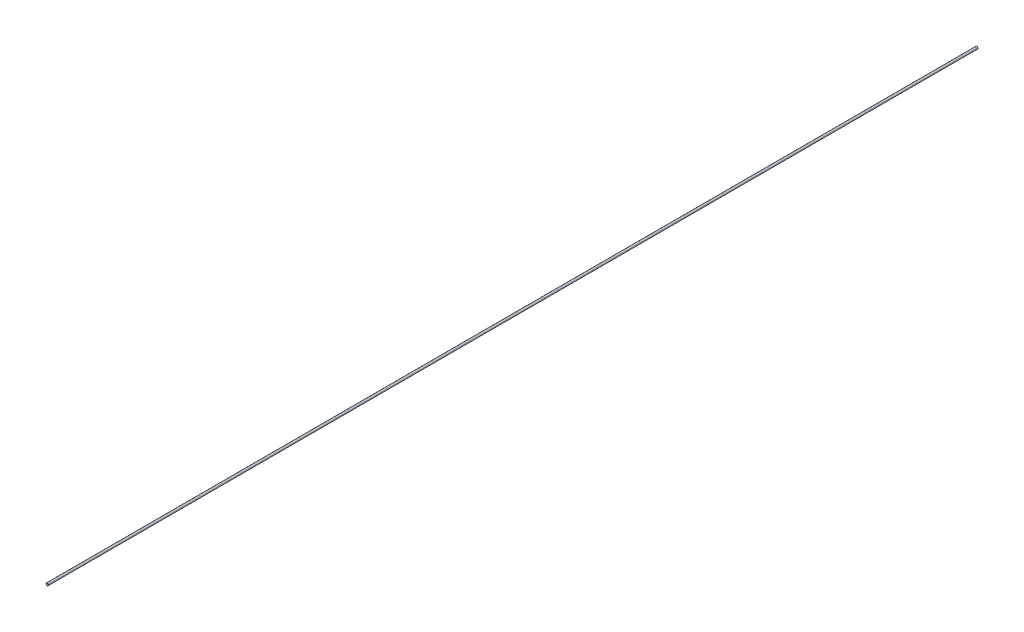
SolidWorks part; units mm, degrees
material "6061-T6 (SS)"
ref_plane "Front Plane" through (0, 0, 0) normal (0, 0, 1) x (1, 0, 0)
ref_plane "Top Plane" through (0, 0, 0) normal (0, 1, 0) x (1, 0, 0)
ref_plane "Right Plane" through (0, 0, 0) normal (1, 0, 0) x (0, 0, -1)
sketch "Sketch1" plane through (0, 0, 0) normal (0, 0, 1) x (1, 0, 0)
  circle A0 centre (0, 0) radius 25.4
  dimension "D1" = 50.8
extrude "Boss-Extrude1" add sketch "Sketch1" against normal blind 20519.088
equation "\"dia\" = 2.00in"
equation "\"F\"= 350"
equation "\"defl\"= .009in"
equation "\"E\"= 10000000"
equation "\"A\"= ( pi * \"dia\" ^ 2 ) / ( 4 )"
equation "\"L\"= ( \"defl\" * pi * \"dia\" ^ 2 * \"E\" ) / ( 4 * \"F\" )"
equation "\"D1@Sketch1\"=\"dia\""
equation "\"D1@Boss-Extrude1\"=\"L\""
